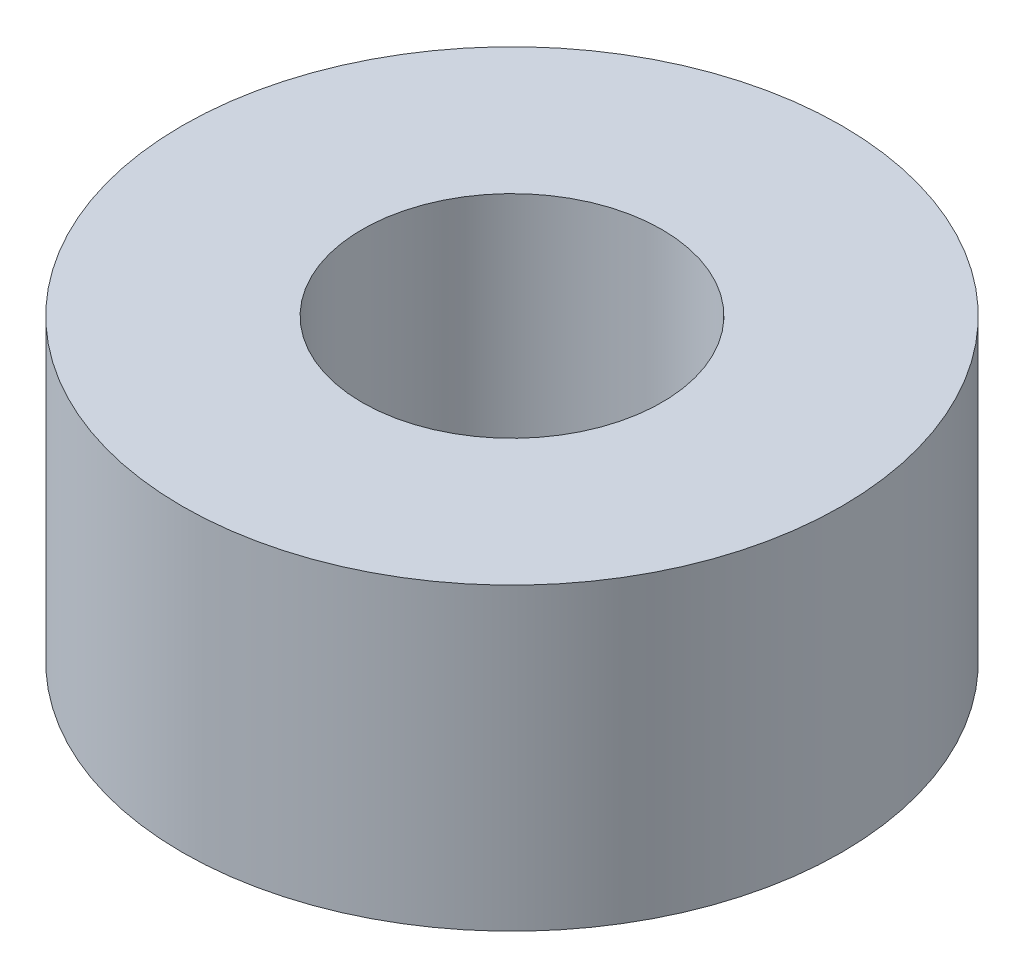
SolidWorks part; units mm, degrees
ref_plane "前视基准面" through (0, 0, 0) normal (0, 0, 1) x (1, 0, 0)
ref_plane "上视基准面" through (0, 0, 0) normal (0, 1, 0) x (1, 0, 0)
ref_plane "右视基准面" through (0, 0, 0) normal (1, 0, 0) x (0, 0, -1)
other "Configuration Table"
sketch "草图1" plane through (0, 0, 0) normal (0, 1, 0) x (1, 0, 0)
  circle A0 centre (0, 0) radius 5.5
  circle A1 centre (0, 0) radius 2.5
  dimension "D1" = 5
  dimension "D2" = 11
extrude "凸台-拉伸1" add sketch "草图1" along normal blind 5 contours A1 | A0
